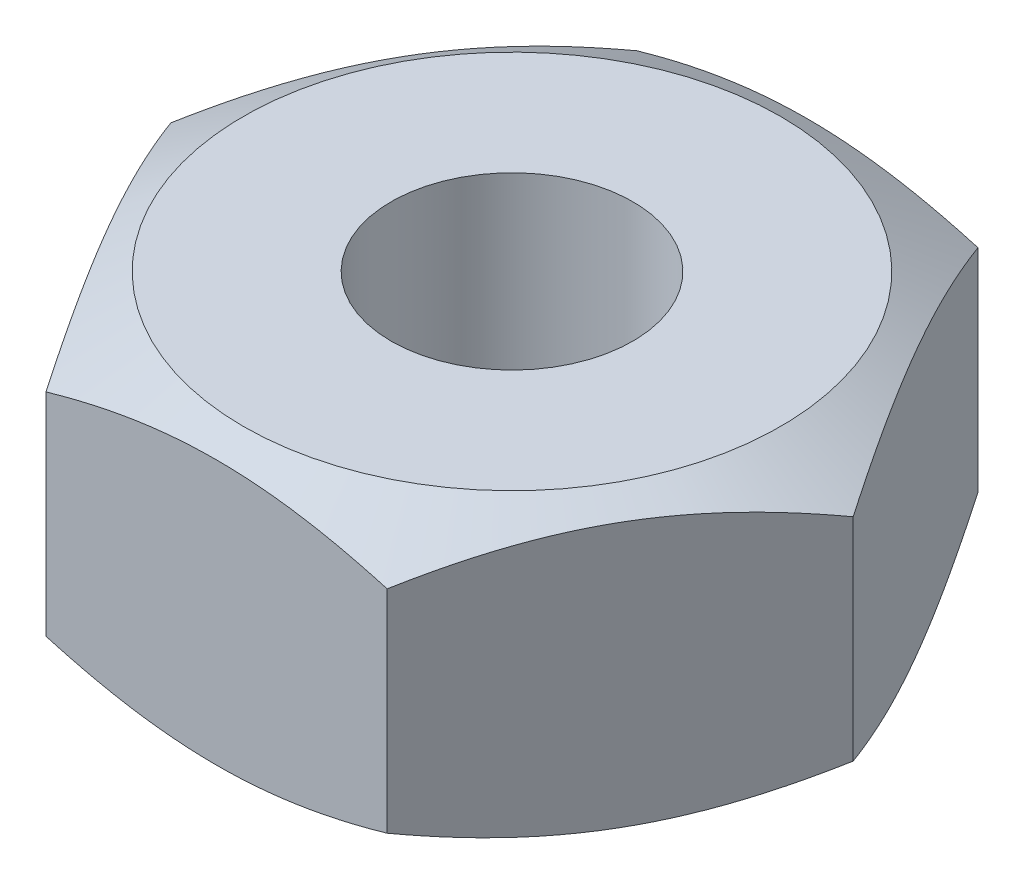
SolidWorks part; units mm, degrees
ref_plane "Alzado" through (0, 0, 0) normal (0, 0, 1) x (1, 0, 0)
ref_plane "Planta" through (0, 0, 0) normal (0, 1, 0) x (1, 0, 0)
ref_plane "Vista lateral" through (0, 0, 0) normal (1, 0, 0) x (0, 0, -1)
sketch "Croquis5" plane through (0, 0, 0) normal (0, 1, 0) x (1, 0, 0)
  line L0 (-12.7017, 0) -> (12.7017, 0) construction
  line L1 (12.7017, 0) -> (6.3509, 11)
  line L2 (6.3509, 11) -> (-6.3509, 11)
  line L3 (-6.3509, 11) -> (-12.7017, 0)
  line L4 (-12.7017, 0) -> (-6.3509, -11)
  line L5 (-6.3509, -11) -> (6.3509, -11)
  line L6 (6.3509, -11) -> (12.7017, 0)
  line L7 (0, 11) -> (0, -11) construction
  circle A0 centre (0, 0) radius 11 construction
  dimension "D1" = 22
extrude "Saliente-Extruir6" add sketch "Croquis5" along normal mid plane 11
sketch "Croquis6" plane through (0, 5.5, 0) normal (0, 1, 0) x (1, 0, 0)
  circle A0 centre (0, 0) radius 4.5
  dimension "D1" = 9
extrude "Cortar-Extruir1" cut sketch "Croquis6" against normal blind 11
sketch "Croquis10" plane through (0, 5.5, 0) normal (0, 1, 0) x (1, 0, 0)
  circle A0 centre (0, 0) radius 10
extrude "Cortar-Extruir2" cut sketch "Croquis10" against normal blind 10 draft 60 flip side to cut
sketch "Croquis11" plane through (0, -5.5, 0) normal (0, -1, 0) x (1, 0, 0)
  circle A0 centre (0, 0) radius 10
extrude "Cortar-Extruir3" cut sketch "Croquis11" against normal blind 10 draft 60 flip side to cut
sketch "Croquis20" plane through (0, 5.5, 0) normal (0, 1, 0) x (1, 0, 0)
  circle A0 centre (0, 0) radius 4.5 construction
  circle A1 centre (0, 0) radius 4.5
